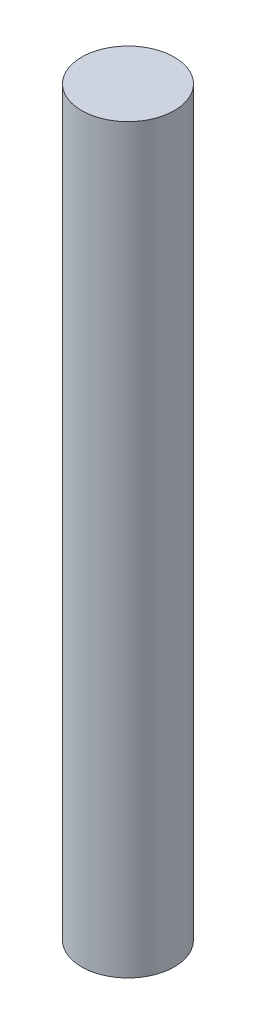
SolidWorks part; units mm, degrees
ref_plane "Front Plane" through (0, 0, 0) normal (0, 0, 1) x (1, 0, 0)
ref_plane "Top Plane" through (0, 0, 0) normal (0, 1, 0) x (1, 0, 0)
ref_plane "Right Plane" through (0, 0, 0) normal (1, 0, 0) x (0, 0, -1)
sketch "Sketch1" plane through (0, 0, 0) normal (0, 1, 0) x (1, 0, 0)
  circle A0 centre (0, 0) radius 6.35
  dimension "D1" = 12.7
extrude "Boss-Extrude1" add sketch "Sketch1" along normal blind 101.6 contours A0
